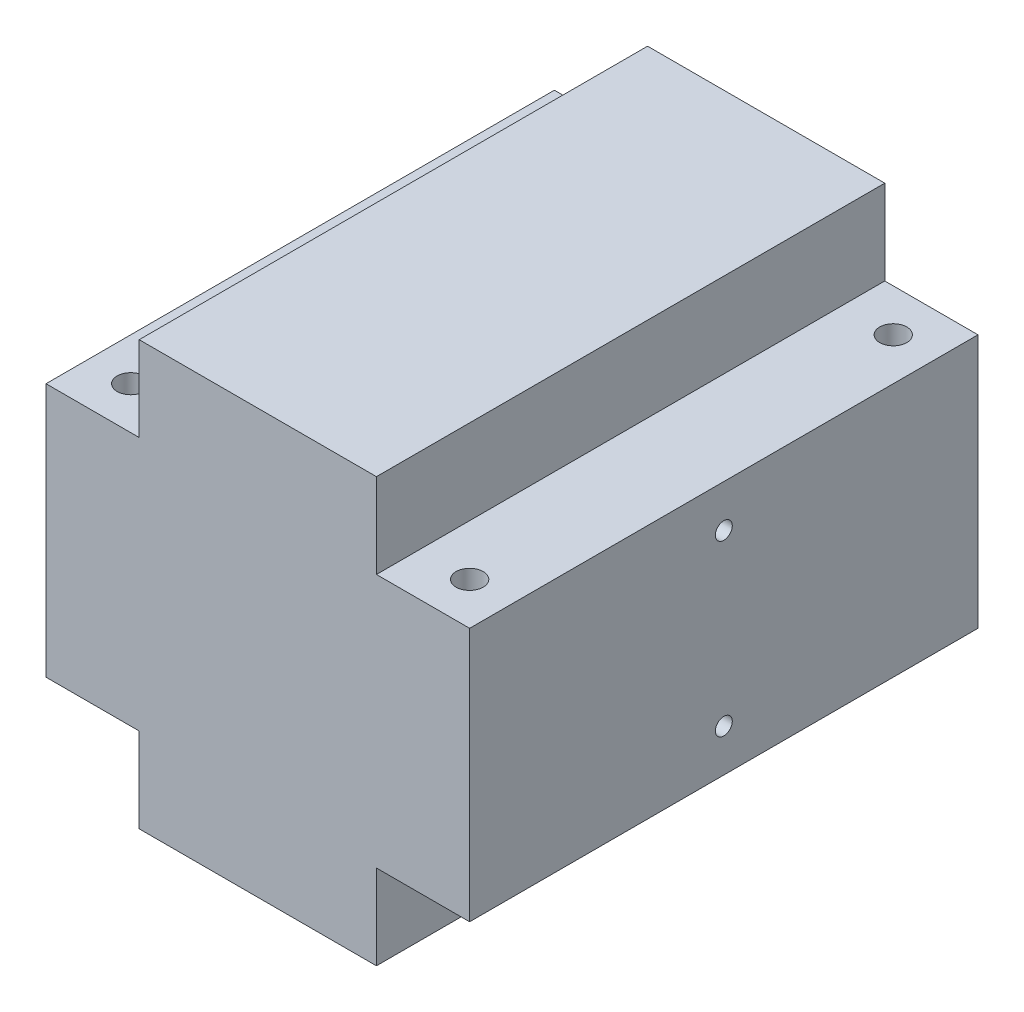
SolidWorks part; units mm, degrees
ref_plane "Front Plane" through (0, 0, 0) normal (0, 0, 1) x (1, 0, 0)
ref_plane "Top Plane" through (0, 0, 0) normal (0, 1, 0) x (1, 0, 0)
ref_plane "Right Plane" through (0, 0, 0) normal (1, 0, 0) x (0, 0, -1)
sketch "Sketch1" plane through (0, 0, 0) normal (0, 0, 1) x (1, 0, 0)
  line L1 (110, 0) -> (390, 0)
  line L2 (0, 100) -> (0, 400)
  line L3 (110, 500) -> (390, 500)
  line L4 (500, 100) -> (500, 400)
  line L5 (0, 100) -> (110, 100)
  line L8 (110, 100) -> (110, 0)
  line L11 (0, 400) -> (110, 400)
  line L12 (110, 500) -> (110, 400)
  line L14 (390, 500) -> (390, 400)
  line L15 (390, 400) -> (500, 400)
  line L17 (500, 100) -> (390, 100)
  line L20 (390, 100) -> (390, 0)
  point P3 (389.3596, 241.3001)
  point P11 (480, 96.9901)
  dimension "D1" = 500
  dimension "D2" = 110
  dimension "D3" = 110
  dimension "D4" = 500
  dimension "D5" = 100
  dimension "D6" = 100
extrude "Boss-Extrude1" add sketch "Sketch1" along normal blind 600
sketch "Sketch5" plane through (0, 100, 0) normal (0, -1, 0) x (-1, 0, 0)
  line L0 (0, 0) -> (-110, 0) construction
  line L1 (0, -600) -> (0, 0) construction
  point P0 (-50, -50)
  point P2 (-50, -550)
  point P4 (-450, -50)
  point P6 (-450, -550)
  point P13 (0, 0)
  point P14 (0, 0)
  point P15 (0, 0)
  point P16 (0, 0)
  dimension "D1" = 50
  dimension "D2" = 500
  dimension "D3" = 400
  dimension "D4" = 50
hole_wizard "M36 Tapped Hole1" positions "Sketch5" profile "Sketch4" tap size "M36" standard "DIN" end condition through all
sketch "Sketch4" plane through (50, 100, 50) normal (1, 0, 0) x (0, 0, -1)
  line L0 (0, 0) -> (0, 400)
  line L1 (0, 400) -> (16, 400)
  line L2 (16, 400) -> (16, 0)
  line L5 (16, 0) -> (0, 0)
  line L11 (0, -6.35) -> (0, 107.95) construction
  dimension "Thru Tap Drill Dia." = 32
  dimension "Thru Tap Drill Depth" = 400
cosmetic thread "Hole Thread1" parameters "D2"=36
cosmetic thread "Hole Thread2" parameters "D2"=36
cosmetic thread "Hole Thread3" parameters "D2"=36
cosmetic thread "Hole Thread4" parameters "D2"=36
sketch "Sketch6" plane through (500, 0, 0) normal (1, 0, 0) x (0, 0, -1)
  line L0 (-600, 100) -> (0, 100) construction
  line L1 (0, 100) -> (0, 400) construction
  circle A0 centre (-300, 150) radius 10
  circle A1 centre (-300, 350) radius 10
  point P4 (0, 0)
  dimension "D1" = 20
  dimension "D2" = 200
  dimension "D3" = 50
  dimension "D4" = 300
extrude "Cut-Extrude1" cut sketch "Sketch6" against normal blind 100 and the other way through all
sketch "Sketch7" plane through (0, 0, 0) normal (-1, 0, 0) x (0, 0, 1)
  circle A0 centre (300, 150) radius 10
  circle A1 centre (300, 350) radius 10
  circle A2 centre (300, 350) radius 10 construction
  circle A3 centre (300, 150) radius 10 construction
extrude "Cut-Extrude2" cut sketch "Sketch7" against normal blind 100
